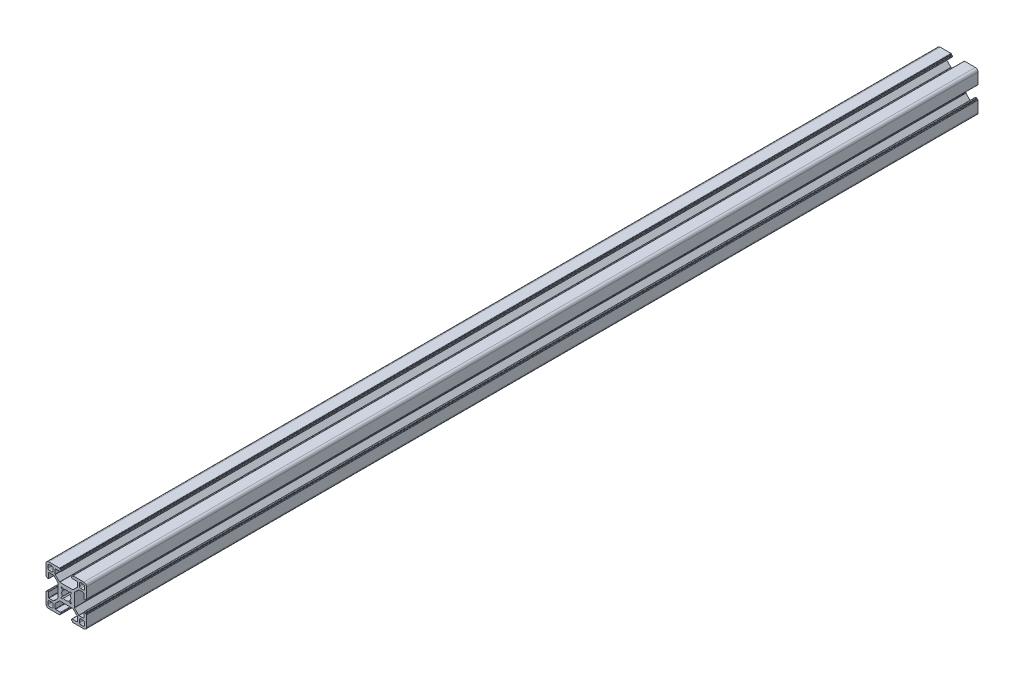
SolidWorks part; units mm, degrees
ref_plane "Piano frontale" through (0, 0, 0) normal (0, 0, 1) x (1, 0, 0)
ref_plane "Piano superiore" through (0, 0, 0) normal (0, 1, 0) x (1, 0, 0)
ref_plane "Piano destro" through (0, 0, 0) normal (1, 0, 0) x (0, 0, -1)
ref_plane "Piano1" through (0, 0, 25) normal (0, 0, 1) x (1, 0, 0)
sketch "Schizzo1" plane through (0, 0, 25) normal (0, 0, 1) x (1, 0, 0)
  line L0 (-12.5625, -9.75) -> (-10.6875, -9.75)
  line L1 (-9.75, -10.6875) -> (-9.75, -12.5625)
  line L2 (-10.6875, -13.5) -> (-12.5625, -13.5)
  line L3 (-13.5, -12.5625) -> (-13.5, -10.6875)
  line L4 (12.5625, 9.75) -> (10.6875, 9.75)
  line L5 (9.75, 10.6875) -> (9.75, 12.5625)
  line L6 (10.6875, 13.5) -> (12.5625, 13.5)
  line L7 (13.5, 12.5625) -> (13.5, 10.6875)
  line L8 (-4.7, -14.7) -> (-4.7, -14.6)
  line L9 (-4.4, -14.3) -> (-4.3, -14.3)
  line L10 (-4, -14) -> (-4, -13.3)
  line L11 (-4.3, -13) -> (-7.95, -13)
  line L12 (-8.25, -12.7) -> (-8.25, -9.4349)
  line L13 (-8.1621, -9.2228) -> (-5.0272, -6.0879)
  line L14 (-4.8151, -6) -> (4.8151, -6)
  line L15 (5.0272, -6.0879) -> (8.1621, -9.2228)
  line L16 (8.25, -9.4349) -> (8.25, -12.7)
  line L17 (7.95, -13) -> (4.3, -13)
  line L18 (4, -13.3) -> (4, -14)
  line L19 (4.3, -14.3) -> (4.4, -14.3)
  line L20 (4.7, -14.6) -> (4.7, -14.7)
  line L21 (5, -15) -> (13, -15)
  line L22 (15, -13) -> (15, -5)
  line L23 (14.7, -4.7) -> (14.6, -4.7)
  line L24 (14.3, -4.4) -> (14.3, -4.3)
  line L25 (14, -4) -> (13.3, -4)
  line L26 (13, -4.3) -> (13, -7.95)
  line L27 (12.7, -8.25) -> (9.4349, -8.25)
  line L28 (9.2228, -8.1621) -> (6.0879, -5.0272)
  line L29 (6, -4.8151) -> (6, 4.8151)
  line L30 (6.0879, 5.0272) -> (9.2228, 8.1621)
  line L31 (9.4349, 8.25) -> (12.7, 8.25)
  line L32 (13, 7.95) -> (13, 4.3)
  line L33 (13.3, 4) -> (14, 4)
  line L34 (14.3, 4.3) -> (14.3, 4.4)
  line L35 (14.6, 4.7) -> (14.7, 4.7)
  line L36 (15, 5) -> (15, 13)
  line L37 (13, 15) -> (5, 15)
  line L38 (4.7, 14.7) -> (4.7, 14.6)
  line L39 (4.4, 14.3) -> (4.3, 14.3)
  line L40 (4, 14) -> (4, 13.3)
  line L41 (4.3, 13) -> (7.95, 13)
  line L42 (8.25, 12.7) -> (8.25, 9.4349)
  line L43 (8.1621, 9.2228) -> (5.0272, 6.0879)
  line L44 (4.8151, 6) -> (-4.8151, 6)
  line L45 (-5.0272, 6.0879) -> (-8.1621, 9.2228)
  line L46 (-8.25, 9.4349) -> (-8.25, 12.7)
  line L47 (-7.95, 13) -> (-4.3, 13)
  line L48 (-4, 13.3) -> (-4, 14)
  line L49 (-4.3, 14.3) -> (-4.4, 14.3)
  line L50 (-4.7, 14.6) -> (-4.7, 14.7)
  line L51 (-5, 15) -> (-13, 15)
  line L52 (-15, 13) -> (-15, 5)
  line L53 (-14.7, 4.7) -> (-14.6, 4.7)
  line L54 (-14.3, 4.4) -> (-14.3, 4.3)
  line L55 (-14, 4) -> (-13.3, 4)
  line L56 (-13, 4.3) -> (-13, 7.95)
  line L57 (-12.7, 8.25) -> (-9.4349, 8.25)
  line L58 (-9.2228, 8.1621) -> (-6.0879, 5.0272)
  line L59 (-6, 4.8151) -> (-6, -4.8151)
  line L60 (-6.0879, -5.0272) -> (-9.2228, -8.1621)
  line L61 (-9.4349, -8.25) -> (-12.7, -8.25)
  line L62 (-13, -7.95) -> (-13, -4.3)
  line L63 (-13.3, -4) -> (-14, -4)
  line L64 (-14.3, -4.3) -> (-14.3, -4.4)
  line L65 (-14.6, -4.7) -> (-14.7, -4.7)
  line L66 (-15, -5) -> (-15, -13)
  line L67 (-13, -15) -> (-5, -15)
  line L68 (2.0101, 2.7422) -> (2.8679, 3.6)
  line L69 (3.6, 2.8679) -> (2.7422, 2.0101)
  line L70 (2.7422, -2.0101) -> (3.6, -2.8679)
  line L71 (2.8679, -3.6) -> (2.0101, -2.7422)
  line L72 (-2.0101, -2.7422) -> (-2.8679, -3.6)
  line L73 (-3.6, -2.8679) -> (-2.7422, -2.0101)
  line L74 (-2.7422, 2.0101) -> (-3.6, 2.8679)
  line L75 (-2.8679, 3.6) -> (-2.0101, 2.7422)
  line L76 (-9.75, 12.5625) -> (-9.75, 10.6875)
  line L77 (-10.6875, 9.75) -> (-12.5625, 9.75)
  line L78 (-13.5, 10.6875) -> (-13.5, 12.5625)
  line L79 (-12.5625, 13.5) -> (-10.6875, 13.5)
  line L80 (9.75, -12.5625) -> (9.75, -10.6875)
  line L81 (10.6875, -9.75) -> (12.5625, -9.75)
  line L82 (13.5, -10.6875) -> (13.5, -12.5625)
  line L83 (12.5625, -13.5) -> (10.6875, -13.5)
  arc A0 (-10.6875, -9.75) -> (-9.75, -10.6875) centre (-10.6875, -10.6875) cw
  arc A1 (-9.75, -12.5625) -> (-10.6875, -13.5) centre (-10.6875, -12.5625) cw
  arc A2 (-12.5625, -13.5) -> (-13.5, -12.5625) centre (-12.5625, -12.5625) cw
  arc A3 (-13.5, -10.6875) -> (-12.5625, -9.75) centre (-12.5625, -10.6875) cw
  arc A4 (10.6875, 9.75) -> (9.75, 10.6875) centre (10.6875, 10.6875) cw
  arc A5 (9.75, 12.5625) -> (10.6875, 13.5) centre (10.6875, 12.5625) cw
  arc A6 (12.5625, 13.5) -> (13.5, 12.5625) centre (12.5625, 12.5625) cw
  arc A7 (13.5, 10.6875) -> (12.5625, 9.75) centre (12.5625, 10.6875) cw
  arc A8 (-5, -15) -> (-4.7, -14.7) centre (-5, -14.7) ccw
  arc A9 (-4.7, -14.6) -> (-4.4, -14.3) centre (-4.4, -14.6) cw
  arc A10 (-4.3, -14.3) -> (-4, -14) centre (-4.3, -14) ccw
  arc A11 (-4, -13.3) -> (-4.3, -13) centre (-4.3, -13.3) ccw
  arc A12 (-7.95, -13) -> (-8.25, -12.7) centre (-7.95, -12.7) cw
  arc A13 (-8.25, -9.4349) -> (-8.1621, -9.2228) centre (-7.95, -9.4349) cw
  arc A14 (-5.0272, -6.0879) -> (-4.8151, -6) centre (-4.8151, -6.3) cw
  arc A15 (4.8151, -6) -> (5.0272, -6.0879) centre (4.8151, -6.3) cw
  arc A16 (8.1621, -9.2228) -> (8.25, -9.4349) centre (7.95, -9.4349) cw
  arc A17 (8.25, -12.7) -> (7.95, -13) centre (7.95, -12.7) cw
  arc A18 (4.3, -13) -> (4, -13.3) centre (4.3, -13.3) ccw
  arc A19 (4, -14) -> (4.3, -14.3) centre (4.3, -14) ccw
  arc A20 (4.4, -14.3) -> (4.7, -14.6) centre (4.4, -14.6) cw
  arc A21 (4.7, -14.7) -> (5, -15) centre (5, -14.7) ccw
  arc A22 (13, -15) -> (15, -13) centre (13, -13) ccw
  arc A23 (15, -5) -> (14.7, -4.7) centre (14.7, -5) ccw
  arc A24 (14.6, -4.7) -> (14.3, -4.4) centre (14.6, -4.4) cw
  arc A25 (14.3, -4.3) -> (14, -4) centre (14, -4.3) ccw
  arc A26 (13.3, -4) -> (13, -4.3) centre (13.3, -4.3) ccw
  arc A27 (13, -7.95) -> (12.7, -8.25) centre (12.7, -7.95) cw
  arc A28 (9.4349, -8.25) -> (9.2228, -8.1621) centre (9.4349, -7.95) cw
  arc A29 (6.0879, -5.0272) -> (6, -4.8151) centre (6.3, -4.8151) cw
  arc A30 (6, 4.8151) -> (6.0879, 5.0272) centre (6.3, 4.8151) cw
  arc A31 (9.2228, 8.1621) -> (9.4349, 8.25) centre (9.4349, 7.95) cw
  arc A32 (12.7, 8.25) -> (13, 7.95) centre (12.7, 7.95) cw
  arc A33 (13, 4.3) -> (13.3, 4) centre (13.3, 4.3) ccw
  arc A34 (14, 4) -> (14.3, 4.3) centre (14, 4.3) ccw
  arc A35 (14.3, 4.4) -> (14.6, 4.7) centre (14.6, 4.4) cw
  arc A36 (14.7, 4.7) -> (15, 5) centre (14.7, 5) ccw
  arc A37 (15, 13) -> (13, 15) centre (13, 13) ccw
  arc A38 (5, 15) -> (4.7, 14.7) centre (5, 14.7) ccw
  arc A39 (4.7, 14.6) -> (4.4, 14.3) centre (4.4, 14.6) cw
  arc A40 (4.3, 14.3) -> (4, 14) centre (4.3, 14) ccw
  arc A41 (4, 13.3) -> (4.3, 13) centre (4.3, 13.3) ccw
  arc A42 (7.95, 13) -> (8.25, 12.7) centre (7.95, 12.7) cw
  arc A43 (8.25, 9.4349) -> (8.1621, 9.2228) centre (7.95, 9.4349) cw
  arc A44 (5.0272, 6.0879) -> (4.8151, 6) centre (4.8151, 6.3) cw
  arc A45 (-4.8151, 6) -> (-5.0272, 6.0879) centre (-4.8151, 6.3) cw
  arc A46 (-8.1621, 9.2228) -> (-8.25, 9.4349) centre (-7.95, 9.4349) cw
  arc A47 (-8.25, 12.7) -> (-7.95, 13) centre (-7.95, 12.7) cw
  arc A48 (-4.3, 13) -> (-4, 13.3) centre (-4.3, 13.3) ccw
  arc A49 (-4, 14) -> (-4.3, 14.3) centre (-4.3, 14) ccw
  arc A50 (-4.4, 14.3) -> (-4.7, 14.6) centre (-4.4, 14.6) cw
  arc A51 (-4.7, 14.7) -> (-5, 15) centre (-5, 14.7) ccw
  arc A52 (-13, 15) -> (-15, 13) centre (-13, 13) ccw
  arc A53 (-15, 5) -> (-14.7, 4.7) centre (-14.7, 5) ccw
  arc A54 (-14.6, 4.7) -> (-14.3, 4.4) centre (-14.6, 4.4) cw
  arc A55 (-14.3, 4.3) -> (-14, 4) centre (-14, 4.3) ccw
  arc A56 (-13.3, 4) -> (-13, 4.3) centre (-13.3, 4.3) ccw
  arc A57 (-13, 7.95) -> (-12.7, 8.25) centre (-12.7, 7.95) cw
  arc A58 (-9.4349, 8.25) -> (-9.2228, 8.1621) centre (-9.4349, 7.95) cw
  arc A59 (-6.0879, 5.0272) -> (-6, 4.8151) centre (-6.3, 4.8151) cw
  arc A60 (-6, -4.8151) -> (-6.0879, -5.0272) centre (-6.3, -4.8151) cw
  arc A61 (-9.2228, -8.1621) -> (-9.4349, -8.25) centre (-9.4349, -7.95) cw
  arc A62 (-12.7, -8.25) -> (-13, -7.95) centre (-12.7, -7.95) cw
  arc A63 (-13, -4.3) -> (-13.3, -4) centre (-13.3, -4.3) ccw
  arc A64 (-14, -4) -> (-14.3, -4.3) centre (-14, -4.3) ccw
  arc A65 (-14.3, -4.4) -> (-14.6, -4.7) centre (-14.6, -4.4) cw
  arc A66 (-14.7, -4.7) -> (-15, -5) centre (-14.7, -5) ccw
  arc A67 (-15, -13) -> (-13, -15) centre (-13, -13) ccw
  arc A68 (2.8679, 3.6) -> (3.6, 2.8679) centre (3.234, 3.234) cw
  arc A69 (2.7422, 2.0101) -> (2.7422, -2.0101) centre (0, 0) cw
  arc A70 (3.6, -2.8679) -> (2.8679, -3.6) centre (3.234, -3.234) cw
  arc A71 (2.0101, -2.7422) -> (-2.0101, -2.7422) centre (0, 0) cw
  arc A72 (-2.8679, -3.6) -> (-3.6, -2.8679) centre (-3.234, -3.234) cw
  arc A73 (-2.7422, -2.0101) -> (-2.7422, 2.0101) centre (0, 0) cw
  arc A74 (-3.6, 2.8679) -> (-2.8679, 3.6) centre (-3.234, 3.234) cw
  arc A75 (-2.0101, 2.7422) -> (2.0101, 2.7422) centre (0, 0) cw
  arc A76 (-9.75, 10.6875) -> (-10.6875, 9.75) centre (-10.6875, 10.6875) cw
  arc A77 (-12.5625, 9.75) -> (-13.5, 10.6875) centre (-12.5625, 10.6875) cw
  arc A78 (-13.5, 12.5625) -> (-12.5625, 13.5) centre (-12.5625, 12.5625) cw
  arc A79 (-10.6875, 13.5) -> (-9.75, 12.5625) centre (-10.6875, 12.5625) cw
  arc A80 (9.75, -10.6875) -> (10.6875, -9.75) centre (10.6875, -10.6875) cw
  arc A81 (12.5625, -9.75) -> (13.5, -10.6875) centre (12.5625, -10.6875) cw
  arc A82 (13.5, -12.5625) -> (12.5625, -13.5) centre (12.5625, -12.5625) cw
  arc A83 (10.6875, -13.5) -> (9.75, -12.5625) centre (10.6875, -12.5625) cw
extrude "Estrusione-Estrusione1" add sketch "Schizzo1" against normal blind 660
